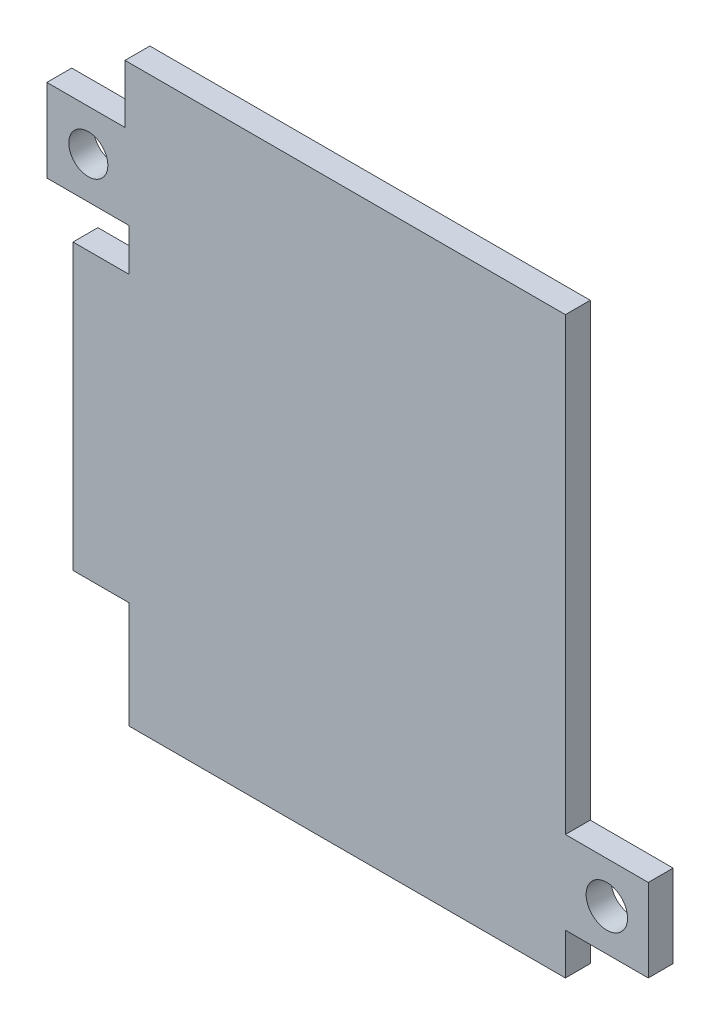
SolidWorks part; units mm, degrees
ref_plane "Front Plane" through (0, 0, 0) normal (0, 0, 1) x (1, 0, 0)
ref_plane "Top Plane" through (0, 0, 0) normal (0, 1, 0) x (1, 0, 0)
ref_plane "Right Plane" through (0, 0, 0) normal (1, 0, 0) x (0, 0, -1)
sketch "Sketch1" plane through (0, 0, 0) normal (0, 0, 1) x (1, 0, 0)
  line L0 (-14.6048, 9.6396) -> (-14.6048, 6.5775)
  line L1 (-14.6048, 6.5775) -> (-18.6584, 6.5775)
  line L2 (-18.6584, 6.5775) -> (-18.6584, -14.0203)
  line L3 (-18.6584, -14.0203) -> (-14.6048, -14.0203)
  line L4 (-14.6048, -14.0203) -> (-14.6048, -21.7504)
  line L5 (-14.6048, -21.7504) -> (16.9952, -21.7504)
  line L6 (16.9952, -21.7504) -> (16.9952, -18.7504)
  line L7 (16.9952, -18.7504) -> (22.9952, -18.7504)
  line L9 (22.9952, -12.7571) -> (16.9952, -12.7504)
  line L10 (16.9952, -12.7504) -> (16.9952, 19.8496)
  line L11 (16.9952, 19.8496) -> (-14.8945, 19.8496)
  line L12 (-14.8945, 19.8496) -> (-14.8945, 15.6396)
  line L13 (-14.8945, 15.6396) -> (-20.5507, 15.6396)
  line L14 (-20.5507, 15.6396) -> (-20.5507, 9.6396)
  line L15 (-20.5507, 9.6396) -> (-14.6048, 9.6396)
  line L16 (22.9952, -18.7504) -> (22.9952, -12.7571)
  circle A0 centre (-17.5507, 12.6396) radius 1.414
  circle A1 centre (19.9952, -15.7539) radius 1.5
  dimension "D1" = 3
  dimension "D2" = 3
  dimension "D3" = 6
  dimension "D4" = 6
  dimension "D5" = 3
  dimension "D6" = 3.0002
  dimension "D7" = 6
  dimension "D8" = 41.6
  dimension "D9" = 31.6
  dimension "D10" = 4.21
  dimension "D11" = 3
extrude "Boss-Extrude1" add sketch "Sketch1" along normal blind 1.8
